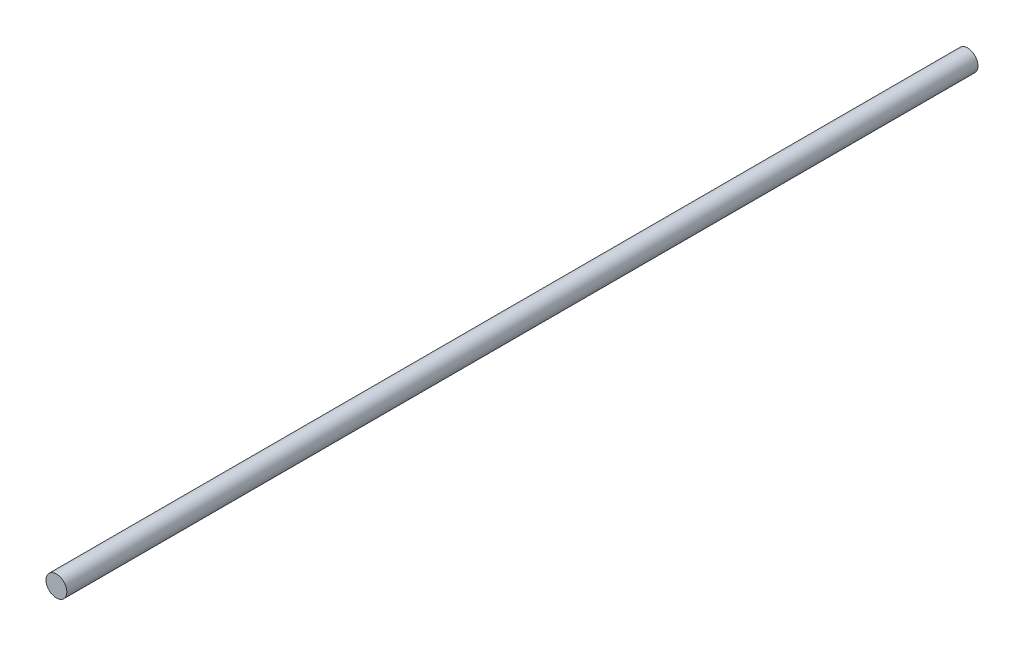
SolidWorks part; units mm, degrees
ref_plane "前基準面" through (0, 0, 0) normal (0, 0, 1) x (1, 0, 0)
ref_plane "上基準面" through (0, 0, 0) normal (0, 1, 0) x (1, 0, 0)
ref_plane "右基準面" through (0, 0, 0) normal (1, 0, 0) x (0, 0, -1)
sketch "草圖1" plane through (0, 0, 0) normal (0, 0, 1) x (1, 0, 0)
  circle A0 centre (0, 0) radius 4
  dimension "D1" = 8
extrude "填料-伸長1" add sketch "草圖1" along normal blind 350
